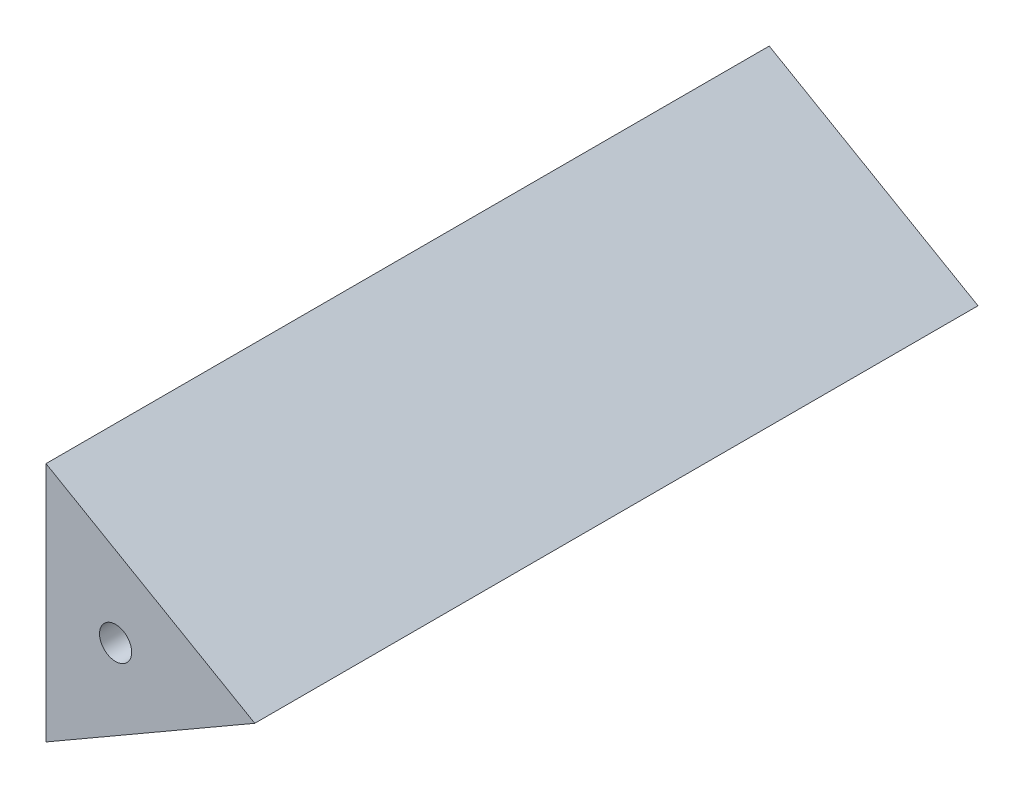
SolidWorks part; units mm, degrees
ref_plane "Front Plane" through (0, 0, 0) normal (0, 0, 1) x (1, 0, 0)
ref_plane "Top Plane" through (0, 0, 0) normal (0, 1, 0) x (1, 0, 0)
ref_plane "Right Plane" through (0, 0, 0) normal (1, 0, 0) x (0, 0, -1)
sketch "Sketch2" plane through (0, 0, 0) normal (0, 0, 1) x (1, 0, 0)
  line L1 (34.64, 0) -> (-17.32, 29.9991)
  line L2 (-17.32, 29.9991) -> (-17.32, -29.9991)
  line L3 (-17.32, -29.9991) -> (34.64, 0)
  circle A0 centre (0, 0) radius 17.32 construction
  circle A1 centre (0, 0) radius 4
extrude "Boss-Extrude2" add sketch "Sketch2" along normal blind 180
